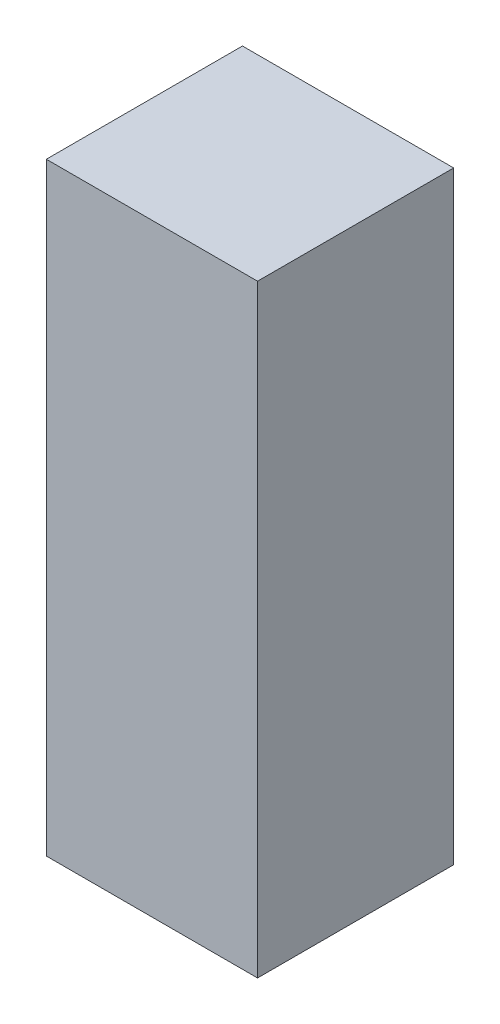
SolidWorks part; units mm, degrees
ref_plane "Front Plane" through (0, 0, 0) normal (0, 0, 1) x (1, 0, 0)
ref_plane "Top Plane" through (0, 0, 0) normal (0, 1, 0) x (1, 0, 0)
ref_plane "Right Plane" through (0, 0, 0) normal (1, 0, 0) x (0, 0, -1)
other "Configuration Table"
sketch "Sketch1" plane through (0, 0, 0) normal (0, 0, 1) x (1, 0, 0)
  line L1 (24, 240) -> (38, 240)
  line L2 (24, 240) -> (24, 280)
  line L3 (24, 280) -> (38, 280)
  line L4 (38, 240) -> (38, 280)
extrude "OVEN_pano_kapagi_mentese_2_1" add sketch "Sketch1" along normal blind 13 from offset 20 separate body
